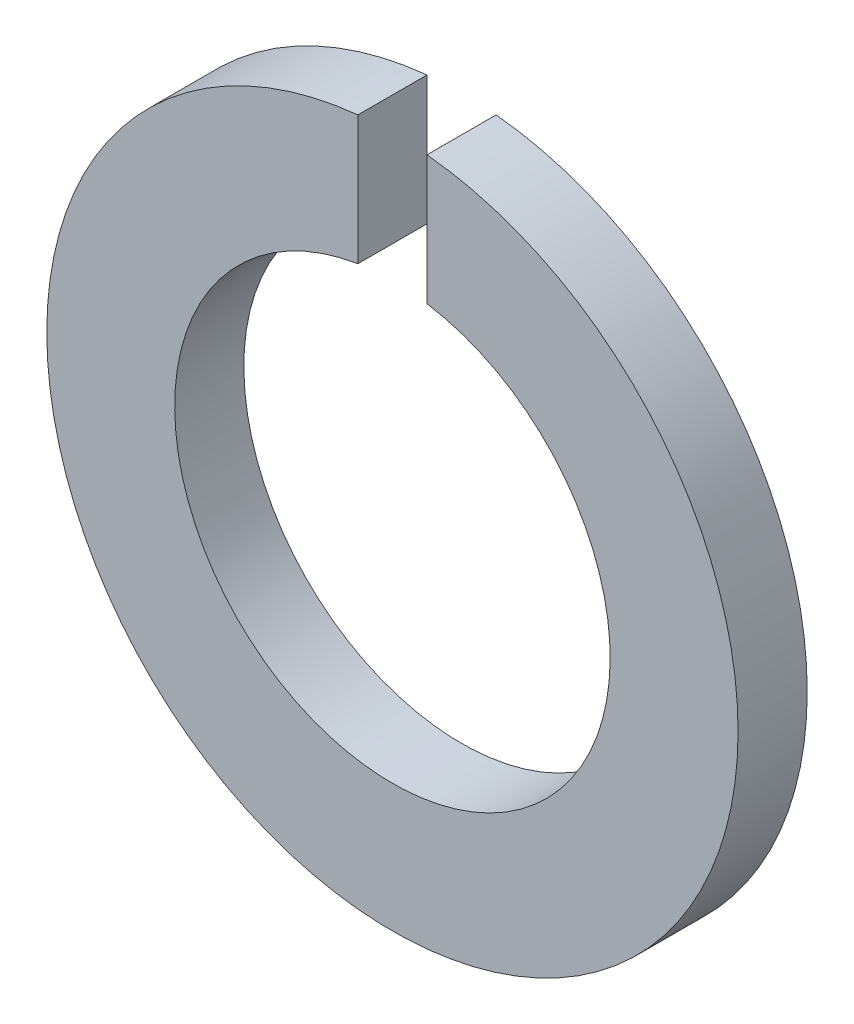
SolidWorks part; units mm, degrees
material "Plain Carbon Steel"
ref_plane "Front Plane" through (0, 0, 0) normal (0, 0, 1) x (1, 0, 0)
ref_plane "Top Plane" through (0, 0, 0) normal (0, 1, 0) x (1, 0, 0)
ref_plane "Right Plane" through (0, 0, 0) normal (1, 0, 0) x (0, 0, -1)
sketch "Sketch1" plane through (0, 0, 0) normal (0, 0, 1) x (1, 0, 0)
  line L0 (0, 0) -> (0, 1.2373) construction
  line L2 (-0.254, 2.5273) -> (-0.254, 1.5797)
  line L4 (0.254, 2.5273) -> (0.254, 1.5797)
  arc A0 (-0.254, 2.5273) -> (0.254, 2.5273) centre (0, 0) ccw
  arc A1 (-0.254, 1.5797) -> (0.254, 1.5797) centre (0, 0) ccw
  dimension "D1" = 5.08
  dimension "D2" = 3.2
extrude "Extrude1" add sketch "Sketch1" along normal blind 0.508
